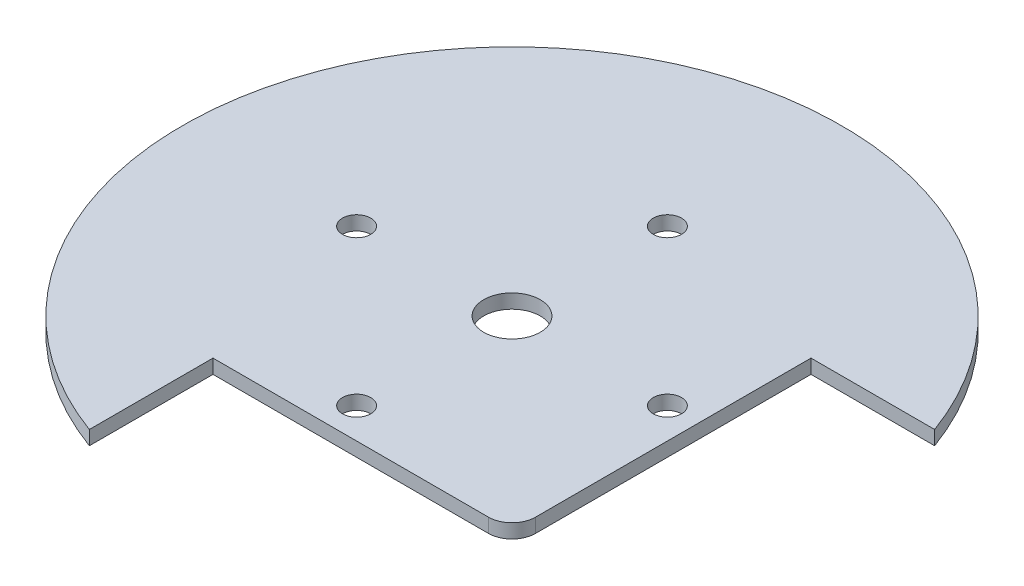
SolidWorks part; units mm, degrees
ref_plane "Front Plane" through (0, 0, 0) normal (0, 0, 1) x (1, 0, 0)
ref_plane "Top Plane" through (0, 0, 0) normal (0, 1, 0) x (1, 0, 0)
ref_plane "Right Plane" through (0, 0, 0) normal (1, 0, 0) x (0, 0, -1)
sketch "Sketch1" plane through (0, 0, 0) normal (0, 1, 0) x (1, 0, 0)
  line L0 (24, -39.5) -> (34.5, -39.5)
  line L1 (-24, -39.5) -> (24, -39.5)
  line L3 (-24, -39.5) -> (-24, -65.7571)
  line L4 (39.5, -34.5) -> (39.5, -24)
  line L10 (39.5, -24) -> (39.5, 24)
  line L11 (39.5, 24) -> (65.7571, 24)
  line L12 (-39.5, 24) -> (-65.7571, 24) [skipped]
  line L13 (-39.5, 24) -> (-39.5, -24) [skipped]
  line L16 (24, 39.5) -> (-24, 39.5) [skipped]
  line L17 (24, 39.5) -> (24, 65.7571) [skipped]
  line L18 (39.5, -24) -> (65.7571, -24) [skipped]
  arc A1 (65.7571, 24) -> (-24, -65.7571) centre (0, 0) ccw
  circle A2 centre (0, 0) radius 6
  circle A4 centre (33, 0) radius 3
  circle A8 centre (0, -33) radius 3
  circle A9 centre (-33, 0) radius 3
  circle A10 centre (0, 33) radius 3
  arc A11 (39.5, -34.5) -> (34.5, -39.5) centre (34.5, -34.5) cw
  point P8 (0, -39.5)
  point P21 (0, 0)
  point P36 (0, 0)
  point P37 (0, 0)
  dimension "D1" = 5
  dimension "D4" = 12
  dimension "D5" = 33
  dimension "D6" = 6
  dimension "D2" = 4
  dimension "D3" = 48
  dimension "D7" = 4
extrude "Boss-Extrude1" add sketch "Sketch1" along normal blind 3
